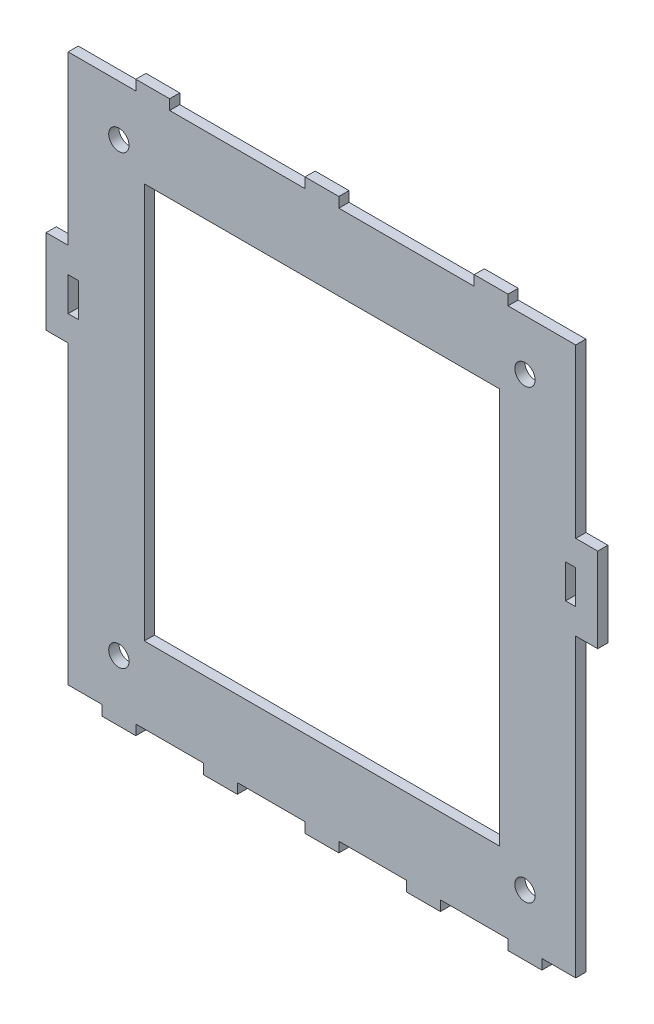
SolidWorks part; units mm, degrees
ref_plane "Front Plane" through (0, 0, 0) normal (0, 0, 1) x (1, 0, 0)
ref_plane "Top Plane" through (0, 0, 0) normal (0, 1, 0) x (1, 0, 0)
ref_plane "Right Plane" through (0, 0, 0) normal (1, 0, 0) x (0, 0, -1)
sketch "Sketch1" plane through (0, 0, 0) normal (0, 0, 1) x (1, 0, 0)
  line L0 (0, 0) -> (0, 65) construction
  line L1 (0, 0) -> (0, -103) construction
  line L2 (-75, 65) -> (0, 65) construction
  line L3 (-75, -103) -> (75, -103) construction
  line L4 (-5, 65) -> (5, 65)
  line L5 (-5, 65) -> (-5, 62)
  line L6 (-5, 62) -> (-45, 62)
  line L7 (-45, 62) -> (-45, 65)
  line L8 (-45, 65) -> (-55, 65)
  line L9 (-55, 65) -> (-55, 62)
  line L10 (-55, 62) -> (-75, 62)
  line L11 (5, 65) -> (5, 62)
  line L12 (5, 65) -> (75, 65) construction
  line L13 (5, 62) -> (45, 62)
  line L14 (45, 62) -> (45, 65)
  line L15 (55, 65) -> (55, 62)
  line L16 (45, 65) -> (55, 65)
  line L17 (55, 62) -> (75, 62)
  line L18 (5, -103) -> (-5, -103)
  line L19 (-5, -103) -> (-5, -100)
  line L20 (-5, -100) -> (-25, -100)
  line L21 (-25, -100) -> (-25, -103)
  line L22 (-25, -103) -> (-35, -103)
  line L23 (-35, -103) -> (-35, -100)
  line L24 (-35, -100) -> (-55, -100)
  line L25 (-55, -100) -> (-55, -103)
  line L26 (-55, -103) -> (-65, -103)
  line L27 (-65, -103) -> (-65, -100)
  line L28 (-65, -100) -> (-75, -100)
  line L29 (5, -103) -> (5, -100)
  line L30 (5, -100) -> (25, -100)
  line L31 (25, -100) -> (25, -103)
  line L32 (25, -103) -> (35, -103)
  line L33 (35, -103) -> (35, -100)
  line L34 (35, -100) -> (55, -100)
  line L35 (55, -100) -> (55, -103)
  line L36 (55, -103) -> (65, -103)
  line L37 (65, -103) -> (65, -100)
  line L38 (65, -100) -> (75, -100)
  line L39 (-75, 62) -> (-75, -100) construction
  line L40 (0, 0) -> (-75, 0) construction
  line L42 (-75, 12.5) -> (-81.5, 12.5)
  line L43 (-81.5, 12.5) -> (-81.5, -12.5)
  line L44 (-81.5, -12.5) -> (-75, -12.5)
  line L45 (-75, 62) -> (-75, 12.5)
  line L50 (-75, -5) -> (-75, 5)
  line L51 (-75, 5) -> (-72, 5)
  line L52 (-75, -12.5) -> (-75, -100)
  line L57 (75, -12.5) -> (75, -100)
  line L58 (81.5, -12.5) -> (75, -12.5)
  line L59 (81.5, 12.5) -> (81.5, -12.5)
  line L60 (75, 12.5) -> (81.5, 12.5)
  line L61 (75, 62) -> (75, 12.5)
  line L62 (-72, 5) -> (-72, -5)
  line L63 (-72, -5) -> (-75, -5)
  line L64 (72, 5) -> (72, -5)
  line L65 (75, 5) -> (72, 5)
  line L66 (75, -5) -> (75, 5)
  line L67 (72, -5) -> (75, -5)
  point P4 (0, 0)
  point P9 (0, 65)
  point P12 (0, -103)
  point P15 (0, 65)
  point P52 (-75, 0)
  point P57 (-75, 0)
  dimension "D1" = 65
  dimension "D2" = 103
  dimension "D3" = 150
  dimension "D4" = 150
  dimension "D5" = 5
  dimension "D6" = 3
  dimension "D7" = 40
  dimension "D8" = 10
  dimension "D9" = 5
  dimension "D10" = 3
  dimension "D11" = 20
  dimension "D12" = 10
  dimension "D13" = 20
  dimension "D14" = 10
  dimension "D15" = 75
  dimension "D16" = 6.5
  dimension "D17" = 25
  dimension "D18" = 10
  dimension "D19" = 3
  dimension "D20" = 49.5
extrude "Boss-Extrude2" add sketch "Sketch1" along normal blind 3
sketch "Sketch2" plane through (0, 0, 3) normal (0, 0, 1) x (1, 0, 0)
  line L0 (-60, 47) -> (60, 47) construction
  line L1 (-60, -85) -> (60, -85) construction
  line L2 (-60, 47) -> (-60, -85) construction
  line L3 (60, 47) -> (60, -85) construction
  line L4 (-75, 62) -> (-75, 12.5) construction
  line L5 (75, 12.5) -> (75, 62) construction
  line L6 (-55, 62) -> (-75, 62) construction
  line L7 (-55, -100) -> (-35, -100) construction
  dimension "D1" = 15
  dimension "D2" = 15
  dimension "D3" = 15
  dimension "D4" = 15
hole_wizard "Ø6.0 (6) Diameter Hole1" positions "Sketch3" profile "Sketch4" hole size "Ø6.0" standard "AS" end condition through all
sketch "Sketch3" plane through (0, 0, 3) normal (0, 0, 1) x (1, 0, 0)
  point P0 (-60, 47)
  point P3 (60, 47)
  point P6 (-60, -85)
  point P9 (60, -85)
sketch "Sketch4" plane through (-60, 47, 3) normal (1, 0, 0) x (0, -1, 0)
  line L0 (0, 0) -> (0, 3)
  line L1 (0, 3) -> (3, 3)
  line L2 (3, 3) -> (3, 0)
  line L5 (3, 0) -> (0, 0)
  line L11 (0, -6.35) -> (0, 107.95) construction
  dimension "Thru Hole Dia." = 6
  dimension "Thru Hole Depth" = 3
sketch "Sketch5" plane through (0, 0, 3) normal (0, 0, 1) x (1, 0, 0)
  line L0 (-52.5, 39.5) -> (-52.5, -77.5)
  line L1 (-52.5, -77.5) -> (52.5, -77.5)
  line L2 (52.5, 39.5) -> (52.5, -77.5)
  line L3 (-52.5, 39.5) -> (52.5, 39.5)
  line L4 (-60, 47) -> (-60, -85) construction
  line L5 (-60, 47) -> (60, 47) construction
  line L6 (-60, -85) -> (60, -85) construction
  line L7 (60, 47) -> (60, -85) construction
  dimension "D1" = 7.5
  dimension "D2" = 7.5
  dimension "D3" = 7.5
  dimension "D4" = 7.5
extrude "Cut-Extrude1" cut sketch "Sketch5" against normal blind 10
